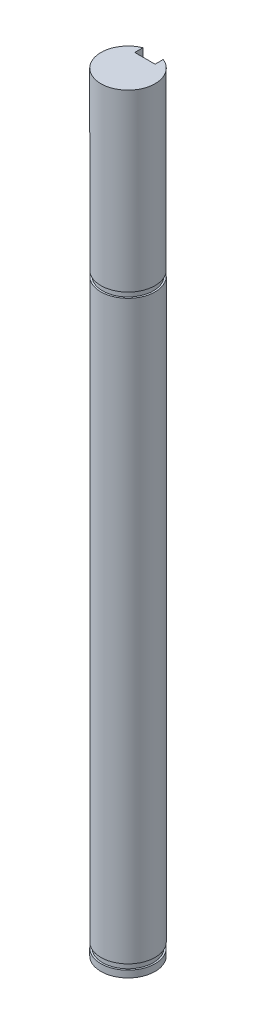
SolidWorks part; units mm, degrees
ref_plane "Front Plane" through (0, 0, 0) normal (0, 0, 1) x (1, 0, 0)
ref_plane "Top Plane" through (0, 0, 0) normal (0, 1, 0) x (1, 0, 0)
ref_plane "Right Plane" through (0, 0, 0) normal (1, 0, 0) x (0, 0, -1)
sketch "Sketch1" plane through (0, 0, 0) normal (0, 1, 0) x (1, 0, 0)
  circle A0 centre (0, 0) radius 4
  dimension "D1" = 8
extrude "Boss-Extrude1" add sketch "Sketch1" along normal blind 111
ref_plane "Plane1" through (0, 86, 0) normal (0, 1, 0) x (1, 0, 0)
sketch "Sketch2" plane through (0, 86, 0) normal (0, 1, 0) x (1, 0, 0)
  circle A0 centre (0, 0) radius 4
  circle A1 centre (0, 0) radius 3.75
  dimension "D1" = 7.5
extrude "Cut-Extrude1" cut sketch "Sketch2" against normal blind 0.8 contours A0 A1
sketch "Sketch3" plane through (0, 0, 0) normal (0, -1, 0) x (-1, 0, 0)
  circle A0 centre (0, 0) radius 3.75
  dimension "D1" = 7.5
sketch "Sketch4" plane through (0, 111, 0) normal (0, 1, 0) x (1, 0, 0)
  circle A0 centre (0, 0) radius 4
extrude "Boss-Extrude3" add sketch "Sketch4" along normal blind 0.85
extrude "Boss-Extrude4" add sketch "Sketch3" along normal blind 0.8
sketch "Sketch5" plane through (0, -0.8, 0) normal (0, -1, 0) x (1, 0, 0)
  circle A0 centre (0, 0) radius 4
extrude "Boss-Extrude5" add sketch "Sketch5" along normal blind 1
sketch "Sketch6" plane through (0, 111.85, 0) normal (0, 1, 0) x (1, 0, 0)
  line L1 (1.5, 5.5) -> (-1.5, 5.5)
  line L2 (1.5, 5.5) -> (1.5, 2.5)
  line L3 (1.5, 2.5) -> (-1.5, 2.5)
  line L4 (-1.5, 5.5) -> (-1.5, 2.5)
  line L5 (1.5, 5.5) -> (-1.5, 2.5) construction
  line L6 (1.5, 2.5) -> (-1.5, 5.5) construction
  circle A0 centre (0, 0) radius 4 construction
  point P0 (0, 4)
  dimension "D1" = 3
  dimension "D2" = 3
extrude "Cut-Extrude2" cut sketch "Sketch6" against normal blind 20
